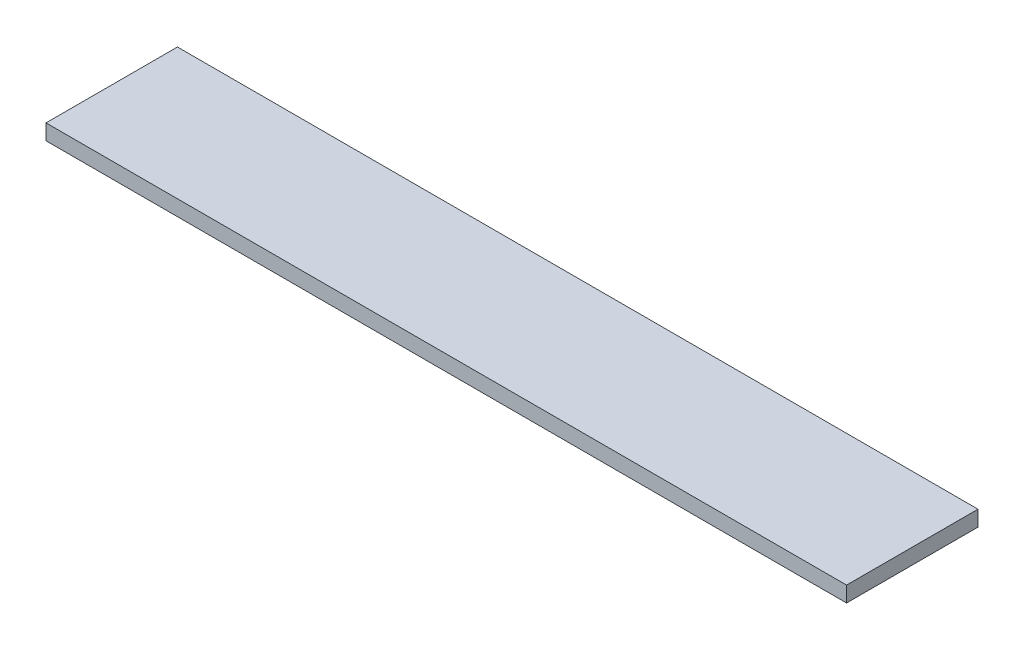
SolidWorks part; units mm, degrees
other "plexiPanel"
ref_plane "Front Plane" through (0, 0, 0) normal (0, 0, 1) x (1, 0, 0)
ref_plane "Top Plane" through (0, 0, 0) normal (0, 1, 0) x (1, 0, 0)
ref_plane "Right Plane" through (0, 0, 0) normal (1, 0, 0) x (0, 0, -1)
sketch "Sketch1" plane through (0, 0, 0) normal (0, 1, 0) x (1, 0, 0)
  line L1 (-15.625, 7.5) -> (51.375, 7.5)
  line L2 (-15.625, 7.5) -> (-15.625, -3.5)
  line L3 (-15.625, -3.5) -> (51.375, -3.5)
  line L4 (51.375, 7.5) -> (51.375, -3.5)
  line L5 (-15.625, 7.5) -> (51.375, -3.5) construction
  line L6 (-15.625, -3.5) -> (51.375, 7.5) construction
  point P4 (17.875, 2)
  dimension "D1" = 11
  dimension "D2" = 67
extrude "Boss-Extrude1" add sketch "Sketch1" along normal blind 1.3
